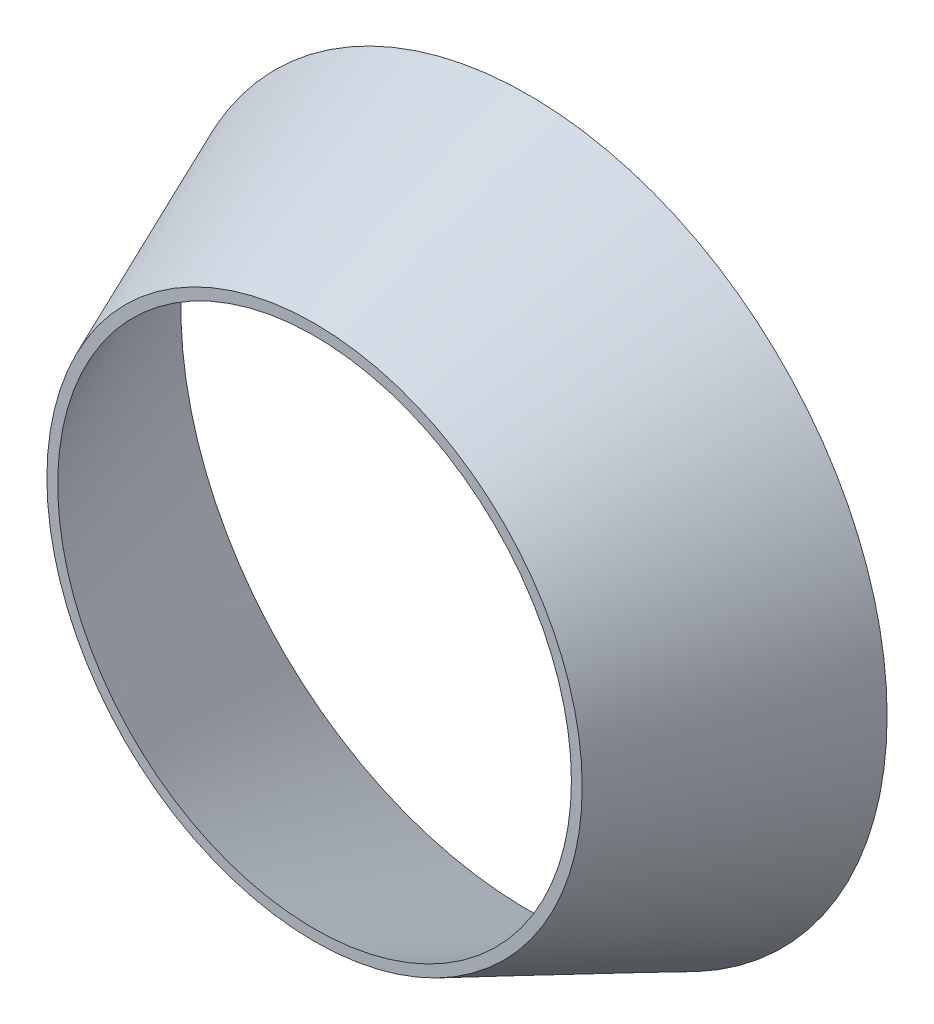
SolidWorks part; units mm, degrees
material "6061-T6 (SS)"
ref_plane "Front Plane" through (0, 0, 0) normal (0, 0, 1) x (1, 0, 0)
ref_plane "Top Plane" through (0, 0, 0) normal (0, 1, 0) x (1, 0, 0)
ref_plane "Right Plane" through (0, 0, 0) normal (1, 0, 0) x (0, 0, -1)
sketch "Sketch1" plane through (0, 0, 0) normal (0, 0, 1) x (1, 0, 0)
  circle A0 centre (0, 0) radius 4953
  circle A1 centre (0, 0) radius 5105.4
  dimension "D1" = 152.4
  dimension "D2" = 10210.8
ref_plane "Plane1" through (0, 0, 3048) normal (0, 0, 1) x (1, 0, 0)
sketch "Sketch2" plane through (0, 0, 3048) normal (0, 0, 1) x (1, 0, 0)
  circle A0 centre (0, 0) radius 3657.6
  circle A1 centre (0, 0) radius 3810
  dimension "D1" = 152.4
  dimension "D2" = 7620
extrude "Boss-Extrude2" add sketch "Sketch1" along normal blind 3048 draft 23 contours A1
extrude "Cut-Extrude1" cut sketch "Sketch2" against normal blind 3048 draft 23 contours A0 draft outward yes
ref_plane "Plane2" through (-4325.9544, 0, 1836.2587) normal (-0.9205, 0, 0.3907) x (0.3907, 0, 0.9205)
sketch "Sketch4" plane through (-4325.9544, 0, 1836.2587) normal (-0.9205, 0, 0.3907) x (0.3907, 0, 0.9205)
  line L0 (-237.2406, 6432.9065) -> (-237.2406, -5470.6033) construction
  text T0 "Team Tribus" font "Engravers MT" height 914.4
wrap "Wrap1" [suppressed] sketch "Sketch4" source sketch "Sketch4" thickness 30.48 parameters "D1"=30.48
